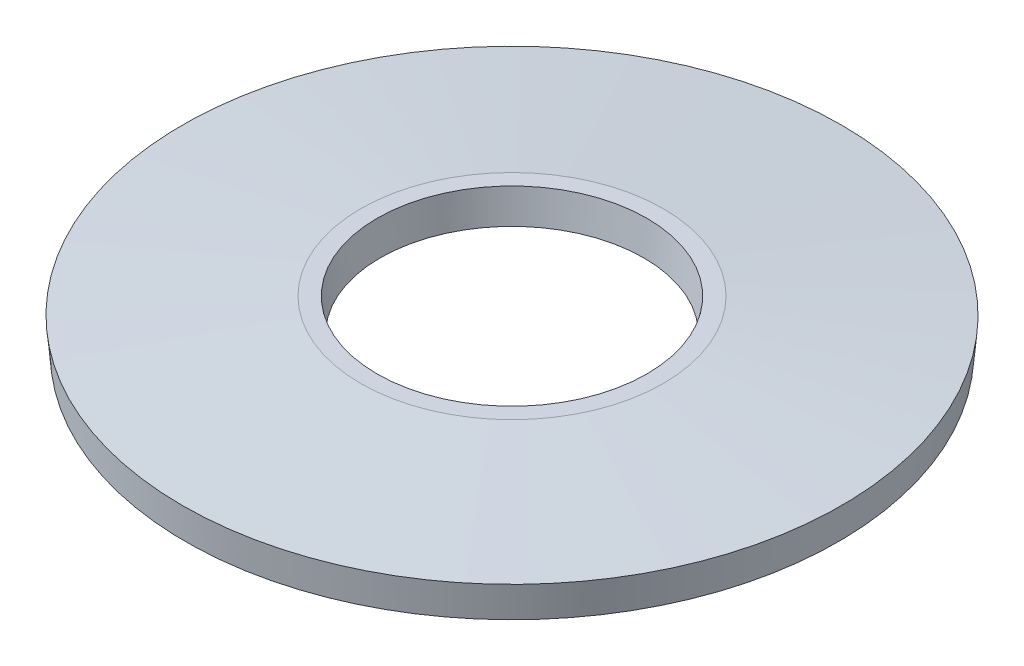
SolidWorks part; units mm, degrees
ref_plane "Front Plane" through (0, 0, 0) normal (0, 0, 1) x (1, 0, 0)
ref_plane "Top Plane" through (0, 0, 0) normal (0, 1, 0) x (1, 0, 0)
ref_plane "Right Plane" through (0, 0, 0) normal (1, 0, 0) x (0, 0, -1)
sketch "Sketch1" plane through (0, 0, 0) normal (0, 0, 1) x (1, 0, 0)
  line L0 (0, 0) -> (0, 0.6) construction
  line L1 (-3.7629, 0) -> (-1.6, 0.2017)
  line L2 (-3.9629, 0) -> (-4, 0.3983)
  line L3 (-1.6, 0.2017) -> (-1.6371, 0.6)
  line L4 (-4, 0.3983) -> (-1.8371, 0.6)
  line L5 (-3.9629, 0) -> (-3.7629, 0)
  line L6 (-1.8371, 0.6) -> (-1.6371, 0.6)
  line L7 (-3.9611, -0.0185) -> (-3.7629, 0) construction
  line L8 (-3.9611, -0.0185) -> (-3.9629, 0) construction
  line L9 (-1.8371, 0.6) -> (-1.6389, 0.6185) construction
  line L10 (-1.6371, 0.6) -> (-1.6389, 0.6185) construction
  dimension "D1" = 0.2
  dimension "D2" = 3.2
  dimension "D3" = 8
  dimension "D4" = 0.4
  dimension "D5" = 0.6
revolve "Revolve1" add sketch "Sketch1" angle 360 about L0
